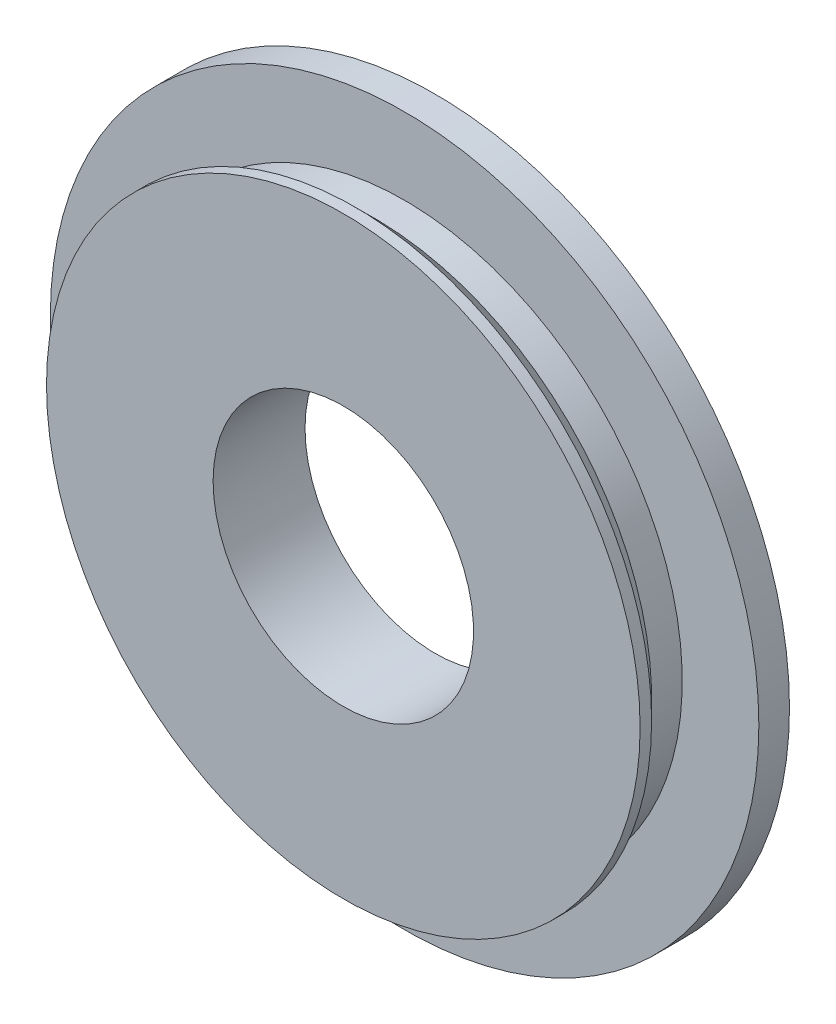
SolidWorks part; units mm, degrees
ref_plane "Front Plane" through (0, 0, 0) normal (0, 0, 1) x (1, 0, 0)
ref_plane "Top Plane" through (0, 0, 0) normal (0, 1, 0) x (1, 0, 0)
ref_plane "Right Plane" through (0, 0, 0) normal (1, 0, 0) x (0, 0, -1)
sketch "Sketch1" plane through (0, 0, 0) normal (0, 1, 0) x (1, 0, 0)
  line L0 (0, 0) -> (3.4, 0) construction
  line L1 (3.4, 0) -> (9.25, 0)
  line L2 (9.25, 0) -> (9.25, -0.8)
  line L3 (9.25, -0.8) -> (7.25, -0.8)
  line L4 (7.25, -0.8) -> (7.25, -1.6)
  line L5 (7.75, -2.4) -> (3.4, -2.4)
  line L6 (3.4, -2.4) -> (3.4, 0)
  line L7 (0, 0.0515) -> (0, -3.2951) construction
  line L8 (7.25, -1.6) -> (7.75, -2.1)
  line L9 (7.75, -2.1) -> (7.75, -2.4)
  dimension "D1" = 3.4
  dimension "D2" = 7.25
  dimension "D3" = 0.8
  dimension "D4" = 2.4
  dimension "D5" = 2
  dimension "D6" = 135
  dimension "D7" = 0.5
revolve "Revolve1" add sketch "Sketch1" angle 360 about L7
sketch "Sketch2" [suppressed] plane through (0, 0, 0) normal (0, 0, -1) x (-1, 0, 0)
  circle A0 centre (0, 0) radius 8.5 construction
  circle A1 centre (-8.5, 0) radius 0.6
  dimension "D1" = 17
  dimension "D2" = 1.2
extrude "Cut-Extrude1" [suppressed] cut sketch "Sketch2" against normal blind 10
sketch "Sketch3" [suppressed] plane through (0, 0, 1.6) normal (0, 0, -1) x (-1, 0, 0)
  line L1 (-8.5, -0.6) -> (-13.9161, -0.6)
  line L2 (-8.5, -0.6) -> (-8.5, 0.6)
  line L3 (-8.5, 0.6) -> (-13.9161, 0.6)
  line L4 (-13.9161, -0.6) -> (-13.9161, 0.6)
  circle A0 centre (-8.5, 0) radius 0.6 construction
  circle A1 centre (-8.5, 0) radius 0.6 construction
extrude "Cut-Extrude2" [suppressed] cut sketch "Sketch3" along normal up to surface (0.8 mm away)
sketch "Sketch4" [suppressed] plane through (0, 0, 2.4) normal (0, 0, 1) x (1, 0, 0)
  line L1 (-19.8376, 5.4) -> (19.4418, 5.4)
  line L2 (-19.8376, 5.4) -> (-19.8376, 25.941)
  line L3 (-19.8376, 25.941) -> (19.4418, 25.941)
  line L4 (19.4418, 5.4) -> (19.4418, 25.941)
  circle A0 centre (0, 0) radius 5.4 construction
  circle A1 centre (0, 0) radius 3.4 construction
  dimension "D1" = 2
extrude "Cut-Extrude3" [suppressed] cut sketch "Sketch4" against normal blind 10
